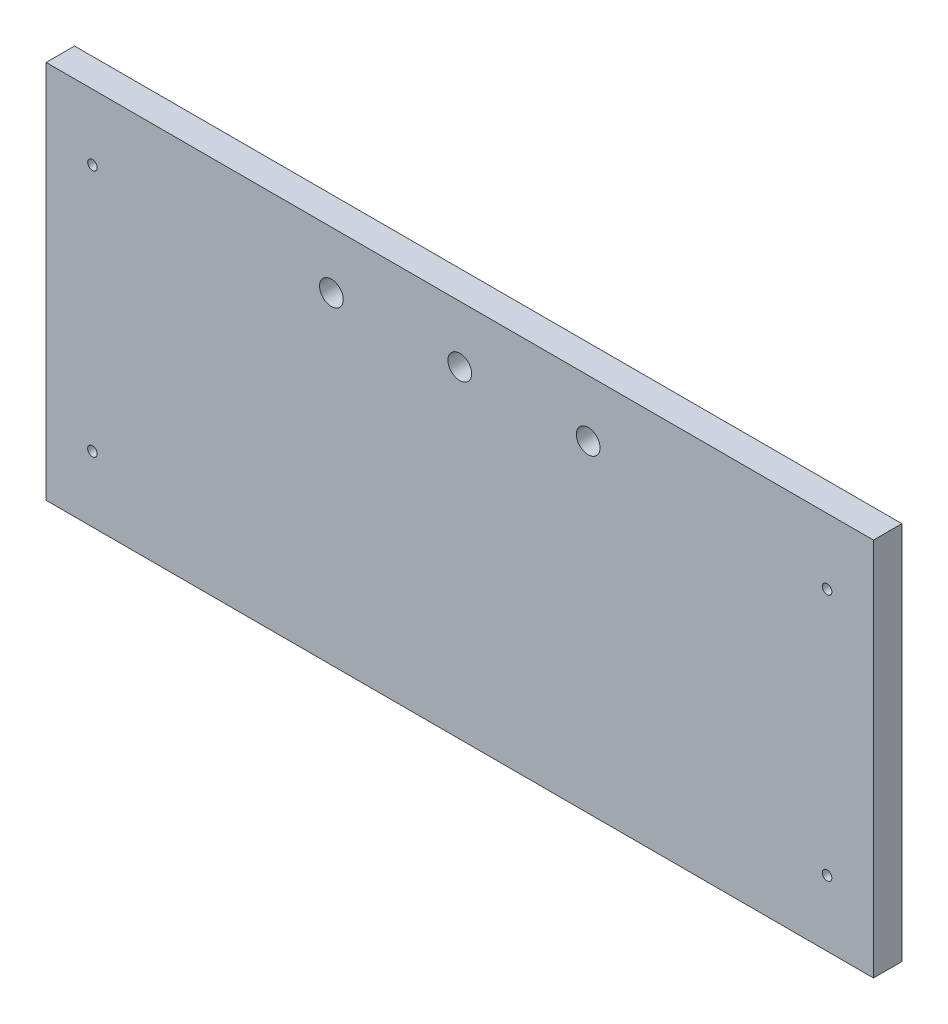
SolidWorks part; units mm, degrees
ref_plane "Front Plane" through (0, 0, 0) normal (0, 0, 1) x (1, 0, 0)
ref_plane "Top Plane" through (0, 0, 0) normal (0, 1, 0) x (1, 0, 0)
ref_plane "Right Plane" through (0, 0, 0) normal (1, 0, 0) x (0, 0, -1)
sketch "Sketch1" plane through (0, 0, 0) normal (0, 0, 1) x (1, 0, 0)
  line L0 (138.525, 127) -> (138.525, 107.95) construction
  line L1 (0, 0) -> (277.05, 0)
  line L2 (0, 0) -> (0, 127)
  line L3 (0, 127) -> (277.05, 127)
  line L4 (277.05, 0) -> (277.05, 127)
  line L5 (9.525, 127) -> (9.525, 0) construction
  line L6 (95.525, 127) -> (95.525, 107.95) construction
  line L7 (267.525, 127) -> (267.525, 0) construction
  line L8 (181.525, 127) -> (181.525, 107.95) construction
  circle A0 centre (95.525, 107.95) radius 3.9687
  circle A1 centre (138.525, 107.95) radius 3.9687
  circle A2 centre (181.525, 107.95) radius 3.9687
  circle A3 centre (15.525, 105) radius 1.6
  circle A4 centre (15.525, 22) radius 1.6
  circle A5 centre (261.525, 105) radius 1.6
  circle A6 centre (261.525, 22) radius 1.6
  dimension "D7" = 7.9375
  dimension "D8" = 7.9375
  dimension "D9" = 7.9375
  dimension "D14" = 3.2
  dimension "D17" = 3.2
  dimension "D19" = 3.2
  dimension "D20" = 3.2
  dimension "D1" = 127
  dimension "D2" = 277.05
  dimension "D3" = 9.525
  dimension "D4" = 86
  dimension "D5" = 9.525
  dimension "D6" = 86
  dimension "D10" = 19.05
  dimension "D11" = 19.05
  dimension "D12" = 19.05
  dimension "D13" = 6
  dimension "D15" = 22
  dimension "D16" = 6
  dimension "D18" = 22
  dimension "D21" = 6
  dimension "D22" = 6
  dimension "D23" = 22
  dimension "D24" = 22
extrude "Boss-Extrude1" add sketch "Sketch1" along normal blind 9.525
equation "\"Length\"= 283mm"
equation "\"Width\"= 225mm"
equation "\"WallThickness\"= 12.5mm"
equation "\"UpperWaterJacketThickness\"= 28mm"
equation "\"SpacerHeight\"= 80.2mm"
equation "\"SpacerCornerWidth\"= 10mm"
equation "\"SpacerCornerHeight\"= 60.16mm"
equation "\"SpacerPegDiameter\"= 10mm"
equation "\"SpacerPegHeight\"= 10mm"
equation "\"TubingShort\"= 110mm"
equation "\"TubingLong\"= 175mm"
equation "\"PlateLength\"= 252mm"
equation "\"PlateWidth\"= 190mm"
equation "\"PlateHoleDiameter\"= 5.9mm"
equation "\"PlateHoleBottom\"= 2mm"
equation "\"PlateHoleSide\"= 1.55mm"
equation "\"PlateHoleSpacing\"= 3.1mm"
equation "\"PlateThickness\"= 1.55mm"
equation "\"ReservoirBottom\"= 12.5mm"
equation "\"ReservoirSupportWidth\"= 12mm"
equation "\"ReservoirSupportHeight\"= 15.1mm"
equation "\"ReservoirSupportPlacementHeight\"= 50mm"
equation "\"ReservoirHoleDiameter\"= 12.7mm"
equation "\"ReservoirHoleRight\"= 25mm"
equation "\"ReservoirHoleTop\"= \"ReservoirSupportPlacementHeight\""
equation "\"ReservoirHeight\"= 90mm"
equation "\"ReservoirPortBottom\"= 4mm"
equation "\"ReservoirPortTop\"= 10mm"
equation "\"ReservoirPortWidth\"= 101mm"
equation "\"CustomSpacerWallThickness\"= 0.375in"
equation "\"CustomSpacerHeight\"= 5in"
equation "\"CustomSpacerRodHoleHeight\"= .75in"
equation "\"CustomSpacerRodHoleDiameter\"= .3125in"
equation "\"ScrewBlockSide\"= 12mm"
equation "\"ScrewBlockUpperHeight\"= 16mm"
equation "\"ScrewBlockLowerHeight\"= 16mm"
equation "\"InternalLength\"= \"Length\" - ( 2 * \"WallThickness\" )"
equation "\"InternalWidth\"= \"Width\" - ( 2 * \"WallThickness\" )"
equation "\"CustomSpacerPegHeight\"= 1in"
equation "\"CustomSpacerScrewBore\"=3.2mm"
equation "\"CustomSpacerScrewDepth\"=10mm"
equation "\"D1@Sketch1\"=\"CustomSpacerHeight\""
equation "\"D2@Sketch1\"=\"InternalLength\"+\"CustomSpacerWallThickness\"*2"
equation "\"D3@Sketch1\"=\"CustomSpacerWallThickness\""
equation "\"D4@Sketch1\"=\"InternalLength\"/3"
equation "\"D5@Sketch1\"=\"CustomSpacerWallThickness\""
equation "\"D6@Sketch1\"=\"InternalLength\"/3"
equation "\"D7@Sketch1\"=\"CustomSpacerRodHoleDiameter\""
equation "\"D8@Sketch1\"=\"CustomSpacerRodHoleDiameter\""
equation "\"D9@Sketch1\"=\"CustomSpacerRodHoleDiameter\""
equation "\"D10@Sketch1\"=\"CustomSpacerRodHoleHeight\""
equation "\"D11@Sketch1\"=\"CustomSpacerRodHoleHeight\""
equation "\"D12@Sketch1\"=\"CustomSpacerRodHoleHeight\""
equation "\"D1@Boss-Extrude1\"=\"CustomSpacerWallThickness\""
equation "\"D13@Sketch1\"=\"ScrewBlockSide\"/2"
equation "\"D14@Sketch1\"=\"CustomSpacerScrewBore\""
equation "\"D15@Sketch1\"=\"ScrewBlockUpperHeight\"+\"ScrewBlockSide\"/2"
equation "\"D16@Sketch1\"=\"ScrewBlockSide\"/2"
equation "\"D17@Sketch1\"=\"CustomSpacerScrewBore\""
equation "\"D18@Sketch1\"=\"ScrewBlockLowerHeight\"+\"ScrewBlockSide\"/2"
equation "\"D19@Sketch1\"=\"CustomSpacerScrewBore\""
equation "\"D20@Sketch1\"=\"CustomSpacerScrewBore\""
equation "\"D21@Sketch1\"=\"ScrewBlockSide\"/2"
equation "\"D22@Sketch1\"=\"ScrewBlockSide\"/2"
equation "\"D23@Sketch1\"=\"ScrewBlockLowerHeight\"+\"ScrewBlockSide\"/2"
equation "\"D24@Sketch1\"=\"ScrewBlockUpperHeight\"+\"ScrewBlockSide\"/2"
